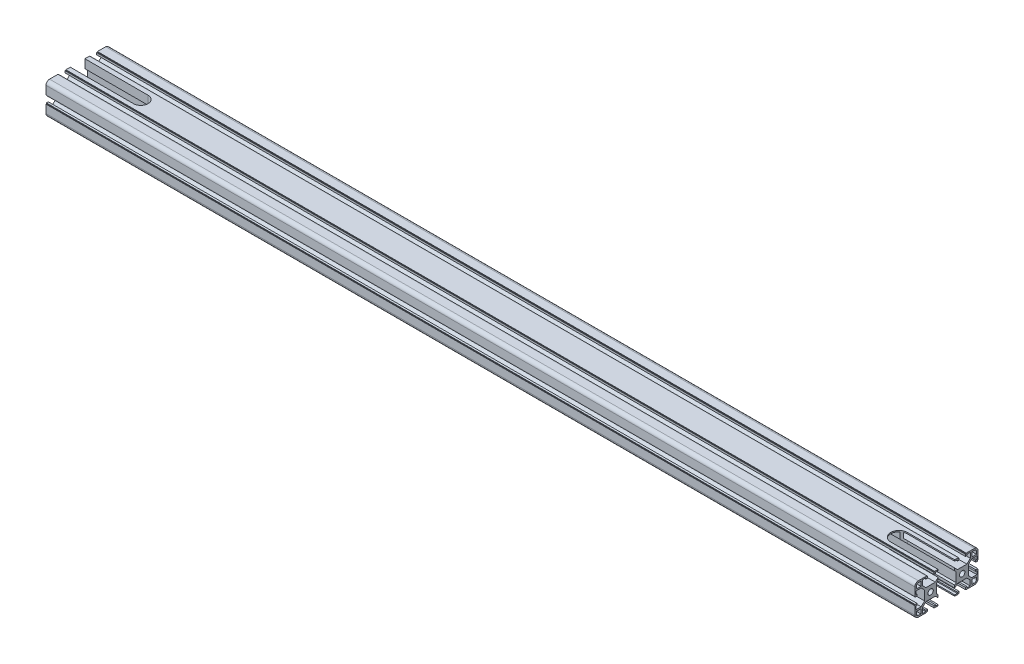
SolidWorks part; units mm, degrees
ref_plane "前视基准面" through (0, 0, 0) normal (0, 0, 1) x (1, 0, 0)
ref_plane "上视基准面" through (0, 0, 0) normal (0, 1, 0) x (1, 0, 0)
ref_plane "右视基准面" through (0, 0, 0) normal (1, 0, 0) x (0, 0, -1)
other "Configuration Table"
sketch "草图1" plane through (0, 0, 0) normal (0, 0, 1) x (1, 0, 0)
  line L0 (-550, 0) -> (550, 0)
  point P4 (0, 0)
  dimension "D1" = 1100
other "工业铝型材 40 X 80W X R4.5(1)"
ref_plane "基准面1" through (-550, 0, 0) normal (1, 0, 0) x (0, 1, 0)
sketch "Sketch1" plane through (-550, 0, 0) normal (1, 0, 0) x (0, 1, 0)
  line L0 (-5.1, 20) -> (-5.1, 19.5)
  line L1 (-5.1, 19.5) -> (-4.1, 19.5)
  line L2 (-4.1, 19.5) -> (-4.1, 17)
  line L3 (-6.1, 18.5) -> (-10.3, 18.5)
  line L4 (0, -20) -> (30.9704, -20) construction
  line L5 (-20, -34.775) -> (-20, -5.1)
  line L6 (15.5, 20) -> (5.1, 20)
  line L7 (20, 15.5) -> (20, 5.1)
  line L8 (0, 14.8756) -> (0, 0) construction
  line L9 (0, 0) -> (14.1675, 0) construction
  line L10 (-10.3, 18.5) -> (-10.3, 12)
  line L11 (-10.3, 12) -> (-6, 7.7)
  line L12 (-6, 7.7) -> (6, 7.7)
  line L13 (10.3, 12) -> (6, 7.7)
  line L14 (10.3, 18.5) -> (10.3, 12)
  line L15 (6.1, 18.5) -> (10.3, 18.5)
  line L16 (4.1, 19.5) -> (4.1, 17)
  line L17 (5.1, 19.5) -> (4.1, 19.5)
  line L18 (5.1, 20) -> (5.1, 19.5)
  line L19 (-5.1, 20) -> (-15.5, 20)
  line L20 (20, 5.1) -> (19.5, 5.1)
  line L21 (12.3, 18) -> (15.5, 18)
  line L22 (12.3, 18) -> (12.3, 12.3)
  line L23 (12.3, 12.3) -> (18, 12.3)
  line L24 (18, 15.5) -> (18, 12.3)
  line L25 (19.5, 5.1) -> (19.5, 4.1)
  line L26 (19.5, 4.1) -> (17, 4.1)
  line L27 (17, 6.1) -> (17, 4.1)
  line L28 (18.5, 6.1) -> (17, 6.1)
  line L29 (18.5, 6.1) -> (18.5, 10.3)
  line L30 (18.5, 10.3) -> (12, 10.3)
  line L31 (12, 10.3) -> (7.7, 6)
  line L32 (7.7, 6) -> (7.7, -6)
  line L33 (12, -10.3) -> (7.7, -6)
  line L34 (18.5, -10.3) -> (12, -10.3)
  line L35 (18.5, -6.1) -> (18.5, -10.3)
  line L36 (18.5, -6.1) -> (17, -6.1)
  line L37 (17, -4.1) -> (17, -6.1)
  line L38 (19.5, -4.1) -> (17, -4.1)
  line L39 (19.5, -5.1) -> (19.5, -4.1)
  line L40 (20, -5.1) -> (19.5, -5.1)
  line L48 (10.325, -12.025) -> (6, -7.7)
  line L49 (6, -7.7) -> (-6, -7.7)
  line L50 (-10.325, -12.025) -> (-6, -7.7)
  line L58 (-20, -5.1) -> (-19.5, -5.1)
  line L60 (-20, 5.1) -> (-20, 15.5)
  line L61 (-19.5, -5.1) -> (-19.5, -4.1)
  line L62 (-6.1, 18.5) -> (-6.1, 17)
  line L63 (-6.1, 17) -> (-4.1, 17)
  line L64 (6.1, 18.5) -> (6.1, 17)
  line L65 (4.1, 17) -> (6.1, 17)
  line L66 (-19.5, -4.1) -> (-17, -4.1)
  line L67 (-15.5, 18) -> (-12.3, 18)
  line L68 (-18, 15.5) -> (-18, 12.3)
  line L69 (-18, 12.3) -> (-12.3, 12.3)
  line L70 (-12.3, 18) -> (-12.3, 12.3)
  line L71 (-17, -6.1) -> (-17, -4.1)
  line L72 (-18.5, -6.1) -> (-17, -6.1)
  line L73 (-18.5, -6.1) -> (-18.5, -10.3)
  line L74 (-18.5, -10.3) -> (-12, -10.3)
  line L75 (-12, -10.3) -> (-7.7, -6)
  line L76 (-7.7, -6) -> (-7.7, 6)
  line L77 (-12, 10.3) -> (-7.7, 6)
  line L78 (-18.5, 10.3) -> (-12, 10.3)
  line L79 (-18.5, 6.1) -> (-18.5, 10.3)
  line L80 (-18.5, 6.1) -> (-17, 6.1)
  line L81 (-17, 4.1) -> (-17, 6.1)
  line L82 (-19.5, 4.1) -> (-17, 4.1)
  line L83 (-19.5, 5.1) -> (-19.5, 4.1)
  line L84 (-20, 5.1) -> (-19.5, 5.1)
  line L85 (20, -5.1) -> (20, -34.9003)
  line L87 (-18.5, -12.025) -> (-10.325, -12.025)
  line L88 (-18.5, -12.025) -> (-18.5, -28)
  line L91 (10.325, -12.025) -> (18.5, -12.025)
  line L94 (18.5, -12.025) -> (18.5, -28)
  line L100 (10.3, -28) -> (18.5, -28)
  line L104 (-18.5, -28) -> (-10.3, -28)
  line L106 (-20, -44.975) -> (-19.5, -44.975)
  line L107 (-19.5, -44.975) -> (-19.5, -43.975)
  line L108 (-19.5, -43.975) -> (-17, -43.975)
  line L109 (-17, -43.975) -> (-17, -45.975)
  line L110 (-18.5, -45.975) -> (-17, -45.975)
  line L111 (-18.5, -45.975) -> (-18.5, -50.175)
  line L112 (-18.5, -50.175) -> (-12, -50.175)
  line L113 (-12, -50.175) -> (-7.7, -45.875)
  line L114 (-7.7, -33.875) -> (-7.7, -45.875)
  line L115 (-12, -29.575) -> (-7.7, -33.875)
  line L116 (-18.5, -29.575) -> (-12, -29.575)
  line L117 (-18.5, -33.775) -> (-18.5, -29.575)
  line L118 (-18.5, -33.775) -> (-17, -33.775)
  line L119 (-17, -33.775) -> (-17, -35.775)
  line L120 (-12.3017, -58) -> (-12.3017, -52.3)
  line L121 (-18.0017, -52.3) -> (-12.3017, -52.3)
  line L122 (-18.0017, -55.5) -> (-18.0017, -52.3)
  line L123 (-15.5017, -58) -> (-12.3017, -58)
  line L124 (-19.5, -35.775) -> (-17, -35.775)
  line L125 (4.1, -57) -> (6.1, -57)
  line L126 (6.1, -58.5) -> (6.1, -57)
  line L127 (-6.1, -57) -> (-4.1, -57)
  line L128 (-6.1, -58.5) -> (-6.1, -57)
  line L129 (-19.5, -34.775) -> (-19.5, -35.775)
  line L130 (-20, -44.975) -> (-20, -55.375)
  line L131 (-20, -34.775) -> (-19.5, -34.775)
  line L138 (-10.3, -28) -> (-6, -32.3)
  line L139 (6, -32.3) -> (-6, -32.3)
  line L140 (10.3, -28) -> (6, -32.3)
  line L147 (20, -34.9003) -> (19.375, -34.8976)
  line L148 (19.375, -34.8976) -> (19.3708, -35.8976)
  line L149 (19.3708, -35.8976) -> (16.8708, -35.8871)
  line L150 (16.8708, -35.8871) -> (16.8792, -33.8872)
  line L151 (18.3792, -33.8935) -> (16.8792, -33.8872)
  line L152 (18.3792, -33.8935) -> (18.3968, -29.6935)
  line L153 (18.3968, -29.6935) -> (11.8969, -29.6662)
  line L154 (11.8969, -29.6662) -> (7.5789, -33.9482)
  line L155 (7.5285, -45.948) -> (7.5789, -33.9482)
  line L156 (11.8105, -50.266) -> (7.5285, -45.948)
  line L157 (18.3104, -50.2933) -> (11.8105, -50.266)
  line L158 (18.328, -46.0933) -> (18.3104, -50.2933)
  line L159 (18.328, -46.0933) -> (16.828, -46.0871)
  line L160 (16.828, -46.0871) -> (16.8364, -44.0871)
  line L161 (19.3364, -44.0976) -> (16.8364, -44.0871)
  line L162 (19.3322, -45.0976) -> (19.3364, -44.0976)
  line L163 (18, -55.5) -> (18, -52.3)
  line L164 (12.3, -52.3) -> (18, -52.3)
  line L165 (12.3, -58) -> (12.3, -52.3)
  line L166 (12.3, -58) -> (15.5, -58)
  line L167 (20, -45.1004) -> (19.3322, -45.0976)
  line L168 (-5.1, -60) -> (-15.5, -60)
  line L169 (5.1, -60) -> (5.1, -59.5)
  line L170 (5.1, -59.5) -> (4.1, -59.5)
  line L171 (4.1, -59.5) -> (4.1, -57)
  line L172 (6.1, -58.5) -> (10.3, -58.5)
  line L173 (10.3, -58.5) -> (10.3, -52)
  line L174 (10.3, -52) -> (6, -47.7)
  line L175 (-6, -47.7) -> (6, -47.7)
  line L176 (-10.3, -52) -> (-6, -47.7)
  line L177 (-10.3, -58.5) -> (-10.3, -52)
  line L178 (20, -55.5) -> (20, -45.1004)
  line L179 (15.5, -60) -> (5.1, -60)
  line L181 (-6.1, -58.5) -> (-10.3, -58.5)
  line L182 (-4.1, -59.5) -> (-4.1, -57)
  line L183 (-5.1, -59.5) -> (-4.1, -59.5)
  line L184 (-5.1, -60) -> (-5.1, -59.5)
  line L185 (5.1, -20) -> (5.1, -19.5) [skipped]
  line L186 (5.1, -19.5) -> (4.1, -19.5) [skipped]
  line L187 (4.1, -19.5) -> (4.1, -17) [skipped]
  line L188 (6.1, -17) -> (4.1, -17) [skipped]
  line L189 (6.1, -18.5) -> (6.1, -17) [skipped]
  line L190 (6.1, -18.5) -> (10.3, -18.5) [skipped]
  line L191 (-6.1, -18.5) -> (-10.3, -18.5) [skipped]
  line L192 (-6.1, -18.5) -> (-6.1, -17) [skipped]
  line L193 (-4.1, -17) -> (-6.1, -17) [skipped]
  line L194 (-4.1, -19.5) -> (-4.1, -17) [skipped]
  line L195 (-5.1, -19.5) -> (-4.1, -19.5) [skipped]
  line L196 (-5.1, -20) -> (-5.1, -19.5) [skipped]
  line L197 (-10.3, -18.5) -> (-10.3, -12) [skipped]
  line L198 (10.3, -18.5) -> (10.3, -12) [skipped]
  circle A0 centre (0, 0) radius 3.4
  arc A1 (-20, 15.5) -> (-15.5, 20) centre (-15.5, 15.5) cw
  arc A2 (20, 15.5) -> (15.5, 20) centre (15.5, 15.5) ccw
  arc A5 (-15.5, 18) -> (-18, 15.5) centre (-15.5, 15.5) ccw
  arc A6 (18, 15.5) -> (15.5, 18) centre (15.5, 15.5) ccw
  arc A11 (18, -55.5) -> (15.5, -58) centre (15.5, -55.5) cw
  arc A12 (-15.5017, -58) -> (-18.0017, -55.5) centre (-15.5017, -55.5) cw
  arc A15 (20, -55.5) -> (15.5, -60) centre (15.5, -55.5) cw
  arc A16 (-20, -55.375) -> (-15.5, -60) centre (-15.5017, -55.5) ccw
  circle A17 centre (0, -40) radius 3.4
  point P2 (0, 10)
  point P4 (0, 0)
  point P7 (20, 20)
  point P8 (-20, 20)
  point P12 (0, 0)
  point P36 (-20, 20)
  point P39 (20, 20)
  dimension "D1" = 20.6
  dimension "D2" = 40
  dimension "D3" = 8.2
  dimension "D4" = 10.2
  dimension "D5" = 12.3
  dimension "D6" = 6.8
  dimension "D7" = 4.5
  dimension "D8" = 45
  dimension "D12" = 2
  dimension "D13" = 5.7
  dimension "D14" = 2
  dimension "D18" = 2.5
  dimension "D19" = 2.5
  dimension "D15" = 80
  dimension "D9" = 0.5
  dimension "D10" = 1.5
  dimension "D11" = 12
  dimension "D16" = 3
  dimension "D17" = 2
  dimension "D20" = 2
  dimension "D21" = 20
  dimension "D22" = 1.725
  dimension "D23" = 20
sketch "草图3" plane through (0, 20, 0) normal (0, 1, 0) x (1, 0, 0)
  line L0 (-550, 20.0001) -> (-470, 20.0001) construction
  line L1 (-550, 34.9003) -> (-550, 5.1) construction
  line L2 (-550, 29.2501) -> (-470, 29.2501)
  line L3 (-550, 10.7501) -> (-470, 10.7501)
  arc A0 (-550, 29.2501) -> (-550, 10.7501) centre (-550, 20.0001) ccw
  arc A1 (-470, 10.7501) -> (-470, 29.2501) centre (-470, 20.0001) ccw
  point P4 (-510, 20.0001)
  dimension "D1" = 18.5
  dimension "D2" = 80
extrude "切除-拉伸1" cut sketch "草图3" against normal up to next
sketch "草图4" plane through (0, 20, 0) normal (0, 1, 0) x (1, 0, 0)
  line L0 (550, 20.0001) -> (490, 20.0001) construction
  line L1 (550, 34.9003) -> (550, 5.1) construction
  line L2 (550, 9.5001) -> (490, 9.5001)
  line L3 (550, 30.5001) -> (490, 30.5001)
  arc A0 (550, 9.5001) -> (550, 30.5001) centre (550, 20.0001) ccw
  arc A1 (490, 30.5001) -> (490, 9.5001) centre (490, 20.0001) ccw
  point P4 (520, 20.0001)
  dimension "D1" = 60
  dimension "D2" = 21
extrude "切除-拉伸2" cut sketch "草图4" against normal through all
equation "\"长\"= 1000mm"
equation "\"宽\"= 300mm"
equation "\"高\"= 500mm"
equation "\"D1@草图1\"=\"长\"+100"
